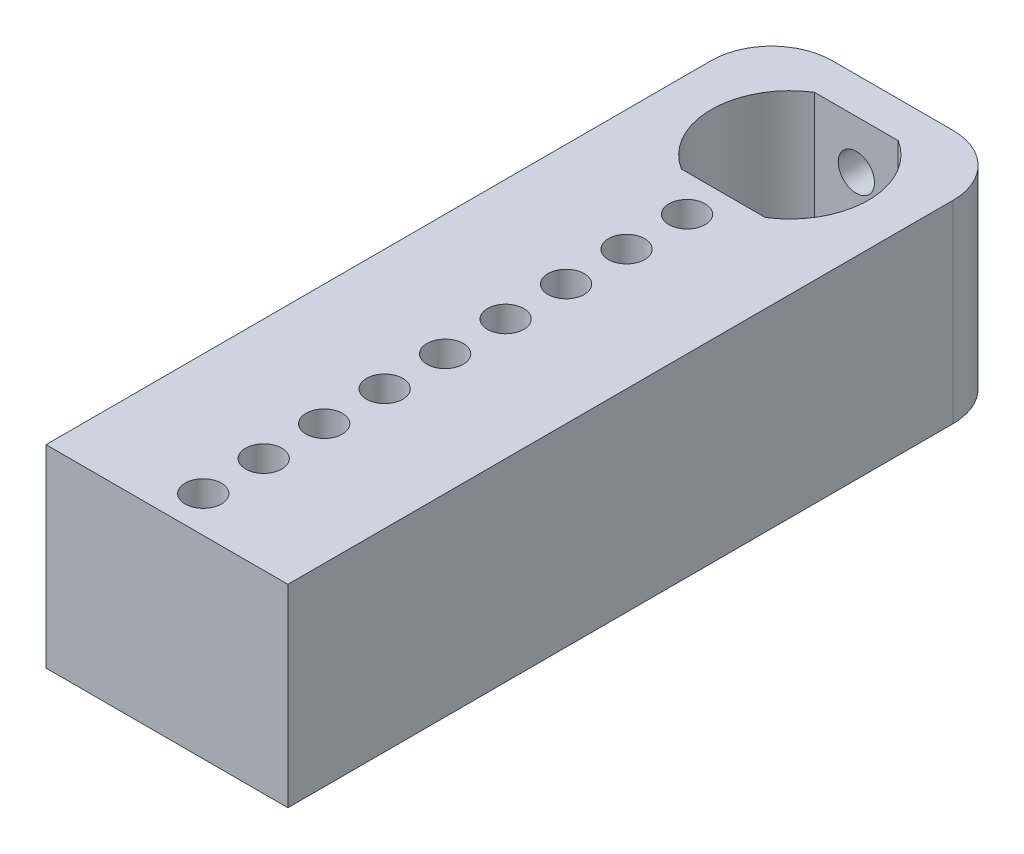
SolidWorks part; units mm, degrees
ref_plane "Alzado" through (0, 0, 0) normal (0, 0, 1) x (1, 0, 0)
ref_plane "Planta" through (0, 0, 0) normal (0, 1, 0) x (1, 0, 0)
ref_plane "Vista lateral" through (0, 0, 0) normal (1, 0, 0) x (0, 0, -1)
sketch "Croquis1" plane through (0, 0, 0) normal (0, 1, 0) x (1, 0, 0)
  line L1 (-10, -30) -> (10, -30)
  line L2 (-10, -30) -> (-10, 30)
  line L3 (-10, 30) -> (10, 30)
  line L4 (10, -30) -> (10, 30)
  line L5 (-10, -30) -> (10, 30) construction
  line L6 (-10, 30) -> (10, -30) construction
  point P0 (0, 0)
  dimension "D1" = 20
  dimension "60" = 60
extrude "Saliente-Extruir1" add sketch "Croquis1" along normal blind 16
sketch "Croquis2" plane through (0, 16, 0) normal (0, 1, 0) x (1, 0, 0)
  line L0 (0, 30) -> (0, 21.5) construction
  line L1 (10, 30) -> (-10, 30) construction
  line L2 (-3.4641, 27) -> (3.4641, 27)
  line L3 (-3.4641, 16) -> (3.4641, 16)
  arc A0 (-3.4641, 27) -> (-3.4641, 16) centre (0, 21.5) ccw
  arc A1 (3.4641, 16) -> (3.4641, 27) centre (0, 21.5) ccw
  dimension "D3" = 13
  dimension "D1" = 5.5
  dimension "D2" = 5.5
  dimension "D4" = 8.5
extrude "Cortar-Extruir1" cut sketch "Croquis2" against normal through all
sketch "Croquis3" plane through (0, 0, -30) normal (0, 0, -1) x (-1, 0, 0)
  line L0 (0, 0) -> (0, 16) construction
  line L1 (-10, 0) -> (10, 0) construction
  line L2 (-10, 16) -> (10, 16) construction
  circle A0 centre (0, 12) radius 1.5
  circle A1 centre (0, 4) radius 1.5
  dimension "D1" = 3
  dimension "D2" = 8
  dimension "D3" = 4
  dimension "D4" = 3
extrude "Cortar-Extruir2" cut sketch "Croquis3" against normal up to surface (3 mm away) up to face at (0, 8, -27)
sketch "Croquis4" plane through (0, 16, 0) normal (0, 1, 0) x (1, 0, 0)
  line L0 (0, 16) -> (0, -30) construction
  line L1 (-3.4641, 16) -> (3.4641, 16) construction
  line L2 (-10, -30) -> (10, -30) construction
  circle A0 centre (0, 13) radius 1.5
  circle A1 centre (0, 8) radius 1.5
  circle A2 centre (0, 3) radius 1.5
  circle A3 centre (0, -2) radius 1.5
  circle A4 centre (0, -7) radius 1.5
  circle A5 centre (0, -12) radius 1.5
  circle A6 centre (0, -17) radius 1.5
  circle A7 centre (0, -22) radius 1.5
  circle A8 centre (0, -27) radius 1.5
  dimension "D1" = 3
  dimension "3" = 3
  dimension "D2" = 9
extrude "Cortar-Extruir3" cut sketch "Croquis4" against normal blind 8
fillet "Redondeo1" radius 5 2 edges at (-10, 8, -30) (10, 8, -30)
